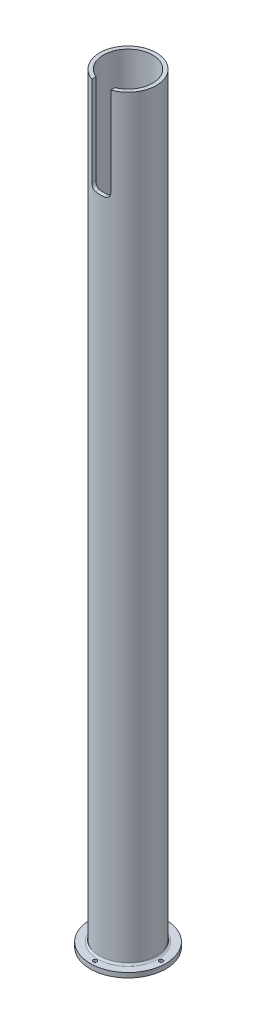
SolidWorks part; units mm, degrees
ref_plane "Front" through (0, 0, 0) normal (0, 0, 1) x (1, 0, 0)
ref_plane "Top" through (0, 0, 0) normal (0, 1, 0) x (1, 0, 0)
ref_plane "Right" through (0, 0, 0) normal (1, 0, 0) x (0, 0, -1)
sketch "Sketch1" plane through (0, 0, 0) normal (0, 1, 0) x (1, 0, 0)
  circle A0 centre (0, 0) radius 30
  circle A1 centre (0, 0) radius 26
  dimension "D1" = 60
  dimension "D2" = 52
extrude "Boss-Extrude1" add sketch "Sketch1" along normal blind 800
sketch "Sketch2" plane through (0, 0, 0) normal (0, -1, 0) x (1, 0, 0)
  circle A0 centre (0, 0) radius 40
  circle A1 centre (0, 0) radius 26 construction
  circle A2 centre (0, 0) radius 26
  circle A3 centre (0, 0) radius 35 construction
  circle A4 centre (0, 35) radius 2
  circle A5 centre (35, 0) radius 2
  circle A6 centre (-35, 0) radius 2
  circle A7 centre (0, -35) radius 2
  dimension "D1" = 80
  dimension "D2" = 70
  dimension "D3" = 4
extrude "Boss-Extrude2" add sketch "Sketch2" along normal blind 5
fillet "Fillet1" radius 2 1 edges at (0, 0, -30)
sketch "Sketch3" plane through (0, 800, 0) normal (0, 1, 0) x (1, 0, 0)
  line L0 (0, 0) -> (0, -59.2423) construction
  line L1 (10, -59.2423) -> (-10, -59.2423)
  line L2 (10, -59.2423) -> (10, -6.1501)
  line L3 (10, -6.1501) -> (-10, -6.1501)
  line L4 (-10, -59.2423) -> (-10, -6.1501)
  dimension "D1" = 20
extrude "Cut-Extrude1" cut sketch "Sketch3" against normal blind 100
fillet "Fillet2" radius 5 2 edges at (-10, 700, 26.1421) (10, 700, 26.1421)
